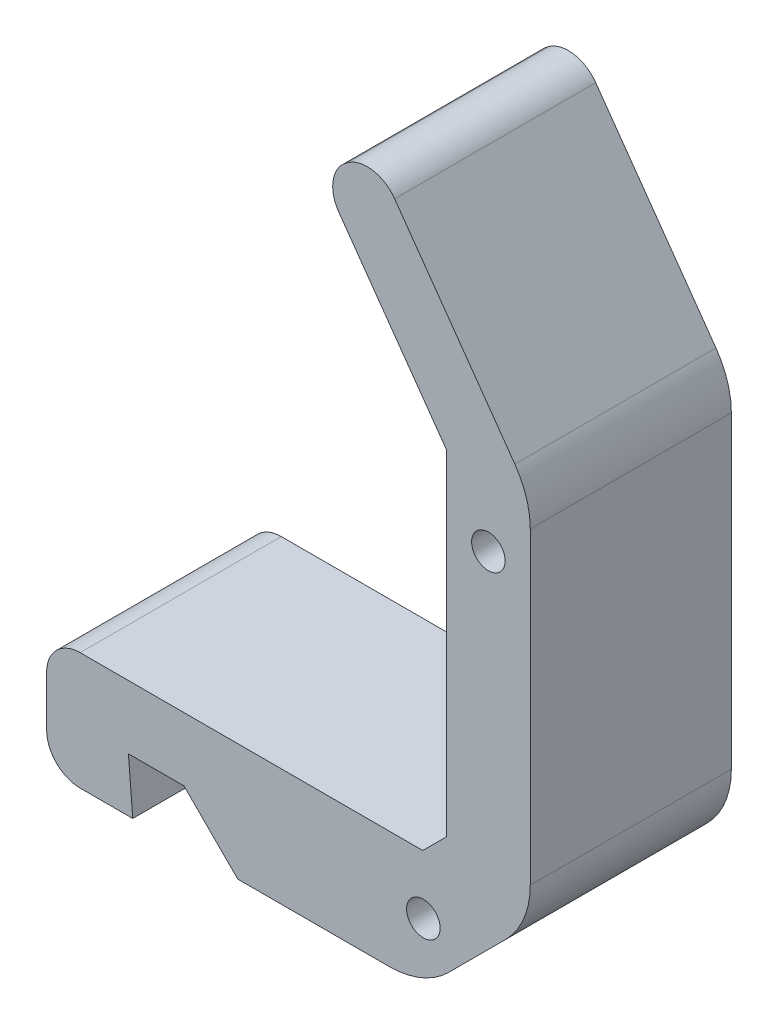
SolidWorks part; units mm, degrees
ref_plane "Front Plane" through (0, 0, 0) normal (0, 0, 1) x (1, 0, 0)
ref_plane "Top Plane" through (0, 0, 0) normal (0, 1, 0) x (1, 0, 0)
ref_plane "Right Plane" through (0, 0, 0) normal (1, 0, 0) x (0, 0, -1)
sketch "Sketch1" plane through (0, 0, 0) normal (0, 0, 1) x (1, 0, 0)
  line L0 (0, 0) -> (-14.1083, 0)
  line L6 (0, 0) -> (-0.0903, 8.89) construction
  line L7 (-18.1908, 4.0824) -> (-22.3991, 4.0824)
  line L8 (-22.3991, 4.0824) -> (-22.0682, 0)
  line L9 (-22.0682, 0) -> (-28.5956, 0)
  line L11 (-28.5956, 0) -> (-28.5956, 8.89)
  line L12 (-0.0903, 8.89) -> (-28.5956, 8.89)
  line L13 (-14.1083, 0) -> (-22.0682, 0) construction
  line L15 (0, 0) -> (8.0558, 8.0558)
  line L16 (8.0558, 8.0558) -> (8.0558, 36.0861)
  line L17 (8.0558, 36.0861) -> (1.7058, 36.0861) construction
  line L18 (1.7058, 36.0861) -> (1.7058, 10.6861)
  line L19 (1.7058, 10.6861) -> (-0.0903, 8.89)
  line L20 (1.7058, 10.6861) -> (8.0558, 8.0558) construction
  line L21 (1.7058, 10.6861) -> (6.1959, 6.1959) construction
  line L22 (1.7058, 31.0061) -> (8.0558, 31.0061) construction
  line L23 (-0.0903, 8.89) -> (-0.0903, 0) construction
  line L24 (-14.1083, 0) -> (-18.1908, 4.0824)
  line L25 (1.7058, 36.0861) -> (-7.9199, 49.67)
  line L26 (-7.9199, 49.67) -> (-3.6925, 52.6655)
  line L27 (-3.6925, 52.6655) -> (8.0558, 36.0861)
  circle A0 centre (-0.0451, 4.445) radius 1.27
  circle A1 centre (4.8808, 31.0061) radius 1.27
  point P21 (-1.9565, 56.7116)
  dimension "D6" = 2.54
  dimension "D4" = 2.54
  dimension "D2" = 6.35
  dimension "D3" = 135
  dimension "D5" = 25.4
  dimension "D7" = 135
  dimension "D8" = 2.54
  dimension "D9" = 5.1811
  dimension "D10" = 20.32
  dimension "D11" = 5.08
  dimension "D12" = 8.89
extrude "Boss-Extrude1" add sketch "Sketch1" along normal blind 15.24
fillet "big_fill" radius 6.35 3 edges at (8.0558, 8.0558, 7.62) (0, 0, 7.62) (8.0558, 36.0861, 7.62)
fillet "Fillet1" radius 2.54 4 edges at (-28.5956, 0, 7.62) (-3.6925, 52.6655, 7.62) (-7.9199, 49.67, 7.62) (-28.5956, 8.89, 7.62)
